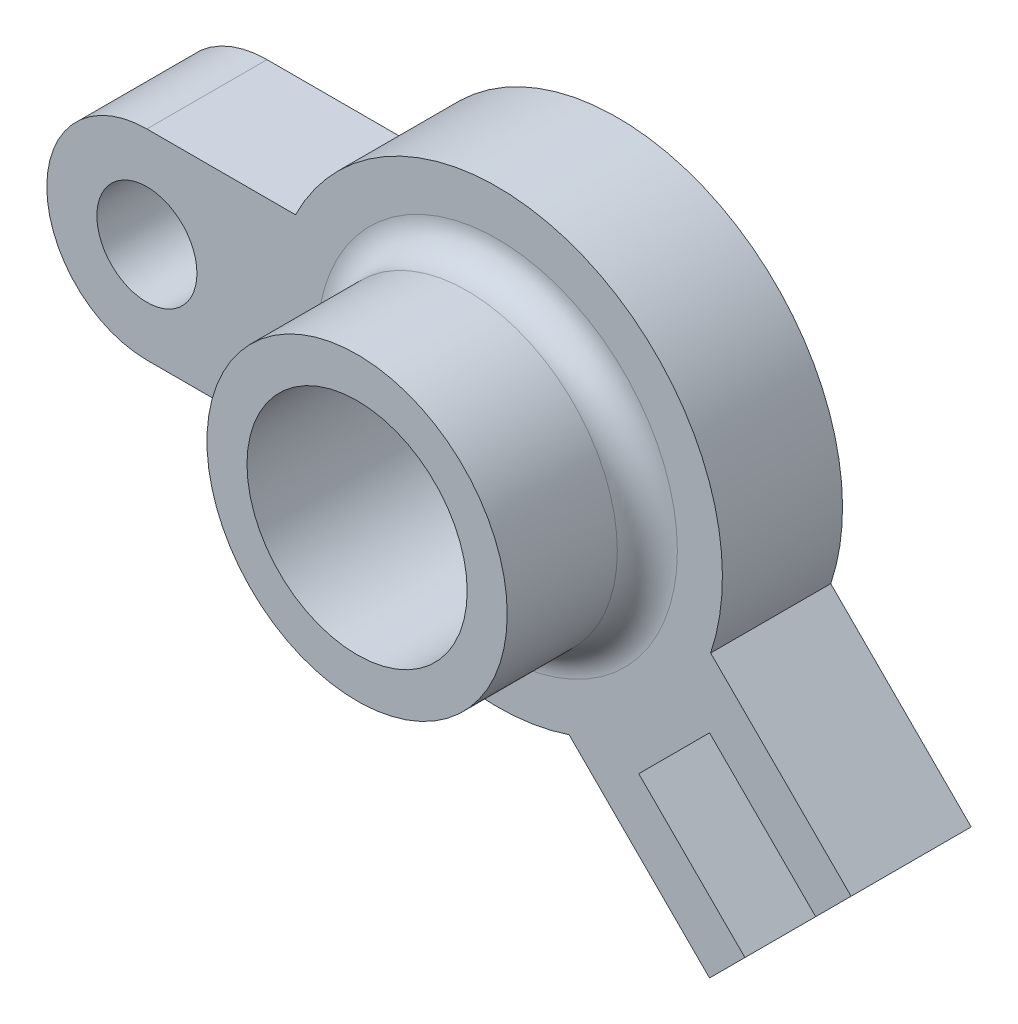
SolidWorks part; units mm, degrees
ref_plane "Alzado" through (0, 0, 0) normal (0, 0, 1) x (1, 0, 0)
ref_plane "Planta" through (0, 0, 0) normal (0, 1, 0) x (1, 0, 0)
ref_plane "Vista lateral" through (0, 0, 0) normal (1, 0, 0) x (0, 0, -1)
sketch "Croquis1" plane through (0, 0, 0) normal (0, 0, 1) x (1, 0, 0)
  line L0 (7.1811, -21.3233) -> (21.2132, -35.3553)
  line L1 (21.3233, -7.1811) -> (35.3553, -21.2132)
  line L2 (35.3553, -21.2132) -> (21.2132, -35.3553)
  line L3 (-20.1556, 10) -> (-35, 10)
  line L4 (-20.1556, -10) -> (-35, -10)
  line L5 (28.2843, -28.2843) -> (0, 0) construction
  line L6 (0, 0) -> (0, -65.3773) construction
  arc A0 (21.3233, -7.1811) -> (-20.1556, 10) centre (0, 0) ccw
  arc A1 (-35, 10) -> (-35, -10) centre (-35, 0) ccw
  arc A2 (-20.1556, -10) -> (7.1811, -21.3233) centre (0, 0) ccw
  dimension "D4" = 45
  dimension "D6" = 20
  dimension "D1" = 45
  dimension "D2" = 40
  dimension "D3" = 20
  dimension "D5" = 35
extrude "Saliente-Extruir1" add sketch "Croquis1" along normal blind 12
sketch "Croquis2" plane through (0, 0, 12) normal (0, 0, 1) x (1, 0, 0)
  circle A0 centre (-35, 0) radius 5
  arc A1 (-35, 10) -> (-35, -10) centre (-35, 0) ccw construction
  dimension "D1" = 10
sketch "Croquis3" plane through (0, 0, 12) normal (0, 0, 1) x (1, 0, 0)
  line L0 (31.8198, -24.7487) -> (21.2132, -14.1421)
  line L1 (21.2132, -35.3553) -> (35.3553, -21.2132) construction
  line L2 (21.2132, -14.1421) -> (14.1421, -21.2132)
  line L3 (14.1421, -21.2132) -> (24.7487, -31.8198)
  line L4 (24.7487, -31.8198) -> (31.8198, -24.7487)
  line L5 (35.3553, -21.2132) -> (21.3233, -7.1811) construction
  dimension "D1" = 15
  dimension "D2" = 10
  dimension "D3" = 5
sketch "Croquis4" plane through (0, 0, 12) normal (0, 0, 1) x (1, 0, 0)
  circle A0 centre (0, 0) radius 15
  dimension "D1" = 30
extrude "Saliente-Extruir2" add sketch "Croquis4" along normal blind 14
sketch "Croquis5" plane through (0, 0, 26) normal (0, 0, 1) x (1, 0, 0)
  circle A0 centre (0, 0) radius 11
  dimension "D1" = 22
extrude "Cortar-Extruir3" cut sketch "Croquis5" against normal blind 18
fillet "Redondeo1" radius 3 1 edges at (15, 0, 12)
extrude "Cortar-Extruir4" cut sketch "Croquis3" against normal blind 8
extrude "Cortar-Extruir6" cut sketch "Croquis2" against normal up to next
